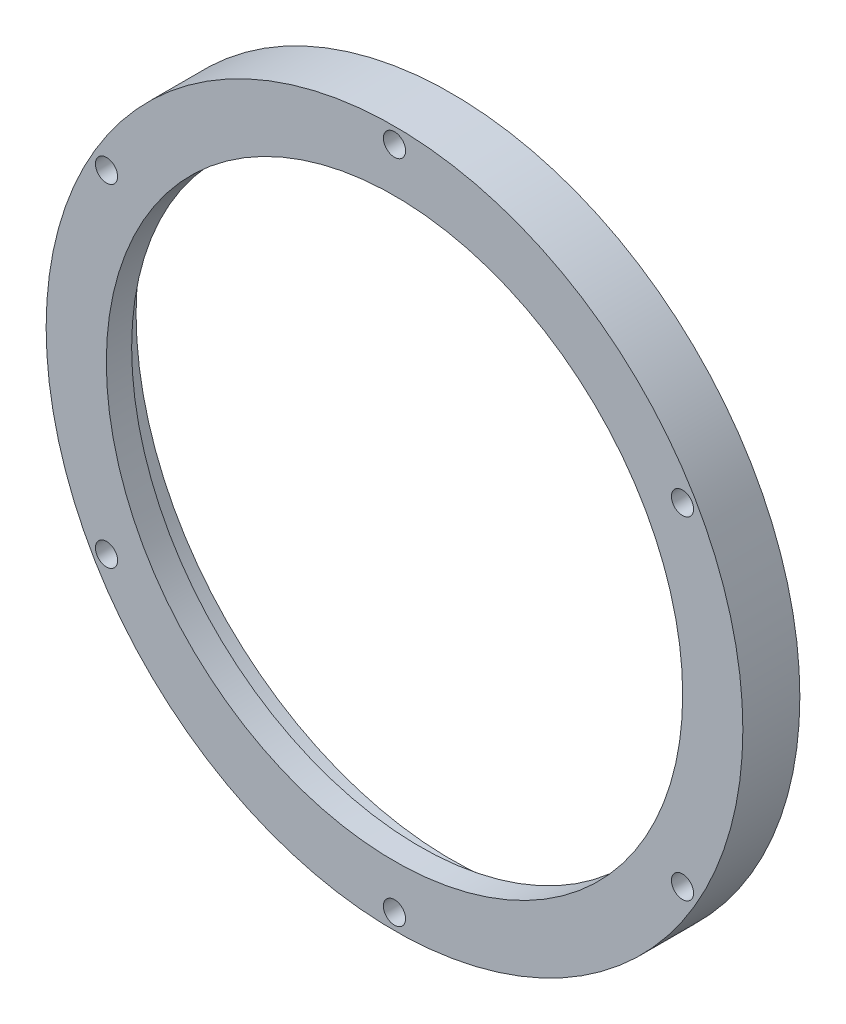
SolidWorks part; units mm, degrees
ref_plane "前视基准面" through (0, 0, 0) normal (0, 0, 1) x (1, 0, 0)
ref_plane "上视基准面" through (0, 0, 0) normal (0, 1, 0) x (1, 0, 0)
ref_plane "右视基准面" through (0, 0, 0) normal (1, 0, 0) x (0, 0, -1)
other "Configuration Table"
sketch "草图1" plane through (0, 0, 0) normal (0, 0, 1) x (1, 0, 0)
  circle A0 centre (0, 0) radius 55
  circle A1 centre (0, 0) radius 45.5
  dimension "D1" = 110
  dimension "D2" = 91
extrude "凸台-拉伸1" add sketch "草图1" along normal blind 9
sketch "草图2" plane through (0, 0, 9) normal (0, 0, 1) x (1, 0, 0)
  circle A0 centre (0, 0) radius 52.5
  circle A1 centre (0, 52.5) radius 1.75
  dimension "D1" = 105
  dimension "D2" = 3.5
extrude "切除-拉伸1" cut sketch "草图2" against normal blind 9 contours A0 A1 | A0 A1
pattern_circular "阵列(圆周)1" count 6 over 360 about axis through (0, 0, 0) along (0, 0, 1) of "切除-拉伸1"
sketch "草图3" plane through (0, 0, 0) normal (0, 1, 0) x (1, 0, 0)
  line L0 (0, 0) -> (0, -9) construction
  line L1 (1.75, 0) -> (-1.75, 0) construction
  line L2 (-55, -9) -> (55, -9) construction
  line L3 (-49.8, 0) -> (-49.8, -5)
  line L4 (55, 0) -> (-55, 0) construction
  line L6 (-46.8307, -5) -> (-45.5, -5)
  line L7 (-45.5, -5) -> (-45.5, 0)
  line L8 (45.5, 0) -> (-45.5, 0) construction
  line L9 (-45.5, 0) -> (-49.8, 0)
  line L12 (-49.8, -5) -> (-46.8307, -5)
  dimension "D1" = 91
  dimension "D2" = 99.6
  dimension "D3" = 5
revolve "切除-旋转1" cut sketch "草图3" angle 360 about L0
